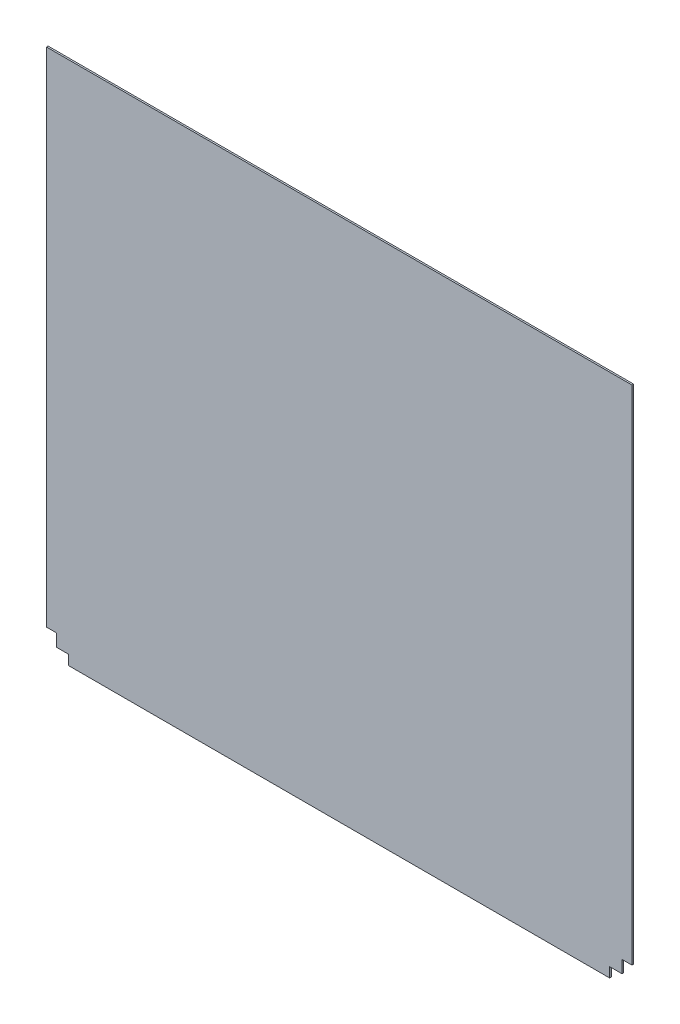
SolidWorks part; units mm, degrees
ref_plane "Front Plane" through (0, 0, 0) normal (0, 0, 1) x (1, 0, 0)
ref_plane "Top Plane" through (0, 0, 0) normal (0, 1, 0) x (1, 0, 0)
ref_plane "Right Plane" through (0, 0, 0) normal (1, 0, 0) x (0, 0, -1)
sketch "Sketch1" plane through (0, 0, 0) normal (0, 0, 1) x (1, 0, 0)
  line L0 (0, 34.544) -> (15.24, 34.544)
  line L1 (0, 0) -> (907.001, 0)
  line L2 (0, 0) -> (0, 812.8)
  line L3 (0, 812.8) -> (907.001, 812.8)
  line L4 (907.001, 0) -> (907.001, 812.8)
  line L5 (0, 0) -> (914.4, 0) construction
  line L6 (0, 0) -> (0, 914.4) construction
  line L7 (0, 914.4) -> (914.4, 914.4) construction
  line L8 (914.4, 0) -> (914.4, 914.4) construction
  line L9 (15.24, 34.544) -> (15.24, 15.24)
  line L10 (15.24, 15.24) -> (34.544, 15.24)
  line L11 (34.544, 15.24) -> (34.544, 0)
  line L12 (907.001, 34.544) -> (891.761, 34.544)
  line L13 (891.761, 34.544) -> (891.761, 15.24)
  line L14 (891.761, 15.24) -> (872.457, 15.24)
  line L15 (872.457, 15.24) -> (872.457, 0)
  dimension "D1" = 812.8
  dimension "D2" = 907.001
  dimension "D3" = 914.4
  dimension "D4" = 914.4
  dimension "D5" = 15.24
  dimension "D6" = 15.24
  dimension "D7" = 34.544
  dimension "D8" = 34.544
  dimension "D9" = 15.24
  dimension "D10" = 15.24
  dimension "D11" = 34.544
  dimension "D12" = 34.544
extrude "Boss-Extrude1" add sketch "Sketch1" along normal blind 2.54 contours L15 L14 L13 L12 L4 L3 L2 L0 L9 L10 L11 L1
